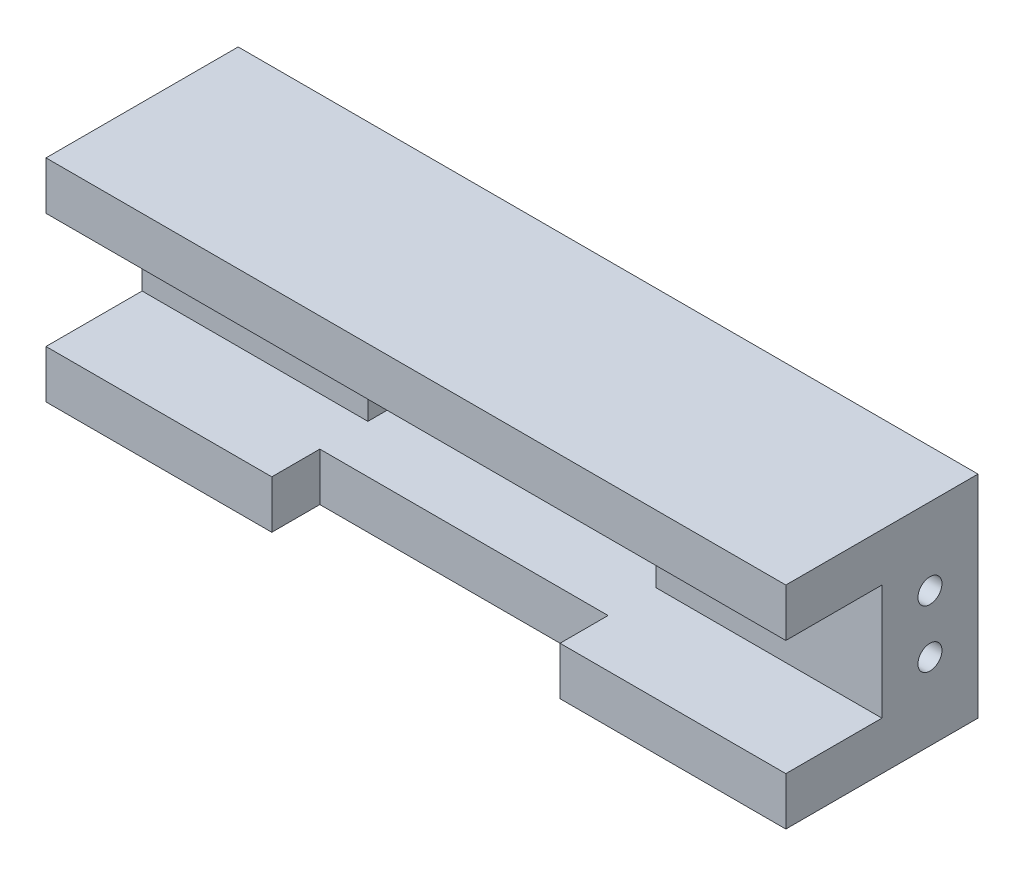
SolidWorks part; units mm, degrees
ref_plane "Front" through (0, 0, 0) normal (0, 0, 1) x (1, 0, 0)
ref_plane "Top" through (0, 0, 0) normal (0, 1, 0) x (1, 0, 0)
ref_plane "Right" through (0, 0, 0) normal (1, 0, 0) x (0, 0, -1)
sketch "Sketch1" plane through (0, 0, 0) normal (0, 0, 1) x (1, 0, 0)
  line L1 (0, 0) -> (77, 0)
  line L2 (0, 0) -> (0, 12)
  line L3 (0, 12) -> (77, 12)
  line L4 (77, 0) -> (77, 12)
  dimension "D1" = 77
  dimension "D2" = 12
extrude "Boss-Extrude1" add sketch "Sketch1" along normal blind 10
sketch "Sketch2" plane through (77, 0, 0) normal (1, 0, 0) x (0, 0, -1)
  line L0 (-5, 0) -> (-5, 12)
  line L1 (-10, 0) -> (0, 0) construction
  line L2 (-10, 12) -> (0, 12) construction
  line L3 (-5, 6) -> (-5, 12)
  line L4 (-5, 6) -> (-5, 0)
  circle A0 centre (-5, 3) radius 1.25
  circle A1 centre (-5, 9) radius 1.25
  dimension "D1" = 3
extrude "Cut-Extrude1" cut sketch "Sketch2" against normal blind 12 contours A0 | A1
ref_plane "Plane1" through (38.5, 0, 0) normal (-1, 0, 0) x (0, 0, 1)
mirror "Mirror1" about plane through (38.5, 0, 0) normal (-1, 0, 0) of "Cut-Extrude1"
sketch "Sketch3" plane through (0, 12, 0) normal (0, 1, 0) x (1, 0, 0)
  line L0 (77, 0) -> (0, 0)
  line L1 (77, 0) -> (77, -20)
  line L2 (0, 0) -> (0, -20)
  line L3 (77, -20) -> (0, -20)
  dimension "D1" = 20
extrude "Boss-Extrude2" add sketch "Sketch3" along normal blind 5
ref_plane "Plane2" through (0, 6, 0) normal (0, -1, 0) x (-1, 0, 0)
mirror "Mirror2" about plane through (0, 6, 0) normal (0, -1, 0) of "Boss-Extrude2"
sketch "Sketch4" plane through (0, 0, 0) normal (0, 0, -1) x (-1, 0, 0)
  line L0 (-77, 6) -> (0, 6)
  line L1 (-77, -5) -> (-77, 17) construction
  line L2 (0, 17) -> (0, -5) construction
  line L3 (-53.5, 12) -> (-53.5, 0)
  line L4 (-53.5, 12) -> (-23.5, 12)
  line L5 (-53.5, 0) -> (-23.5, 0)
  line L6 (-23.5, 12) -> (-23.5, 0)
  line L7 (-53.5, 12) -> (-23.5, 0) construction
  line L8 (-53.5, 0) -> (-23.5, 12) construction
  point P7 (-38.5, 6)
  dimension "D1" = 12
  dimension "D2" = 30
  dimension "D3" = 38.5
extrude "Cut-Extrude2" cut sketch "Sketch4" against normal blind 10 contours L6 L4 L3 L0 | L6 L0 L3 L5
sketch "Sketch5" plane through (0, 0, 20) normal (0, 0, 1) x (1, 0, 0)
  line L0 (0, -2.5) -> (77, -2.5)
  line L1 (0, -5) -> (0, 0) construction
  line L2 (77, -5) -> (77, 0) construction
  line L3 (23.5, -5) -> (23.5, 0)
  line L4 (23.5, -5) -> (53.5, -5)
  line L5 (23.5, 0) -> (53.5, 0)
  line L6 (53.5, -5) -> (53.5, 0)
  line L7 (23.5, -5) -> (53.5, 0) construction
  line L8 (23.5, 0) -> (53.5, -5) construction
  line L9 (0, 12) -> (0, 0) construction
  point P6 (0, 0)
  point P7 (38.5, -2.5)
  line M2 (77, 0) -> (0, 0)
  line M4 (0, -5) -> (77, -5)
  dimension "D1" = 30
  dimension "D2" = 38.5
extrude "Cut-Extrude3" cut sketch "Sketch5" against normal blind 5 contours L0 L6 L3 M2 | L6 L0 L3 M4
